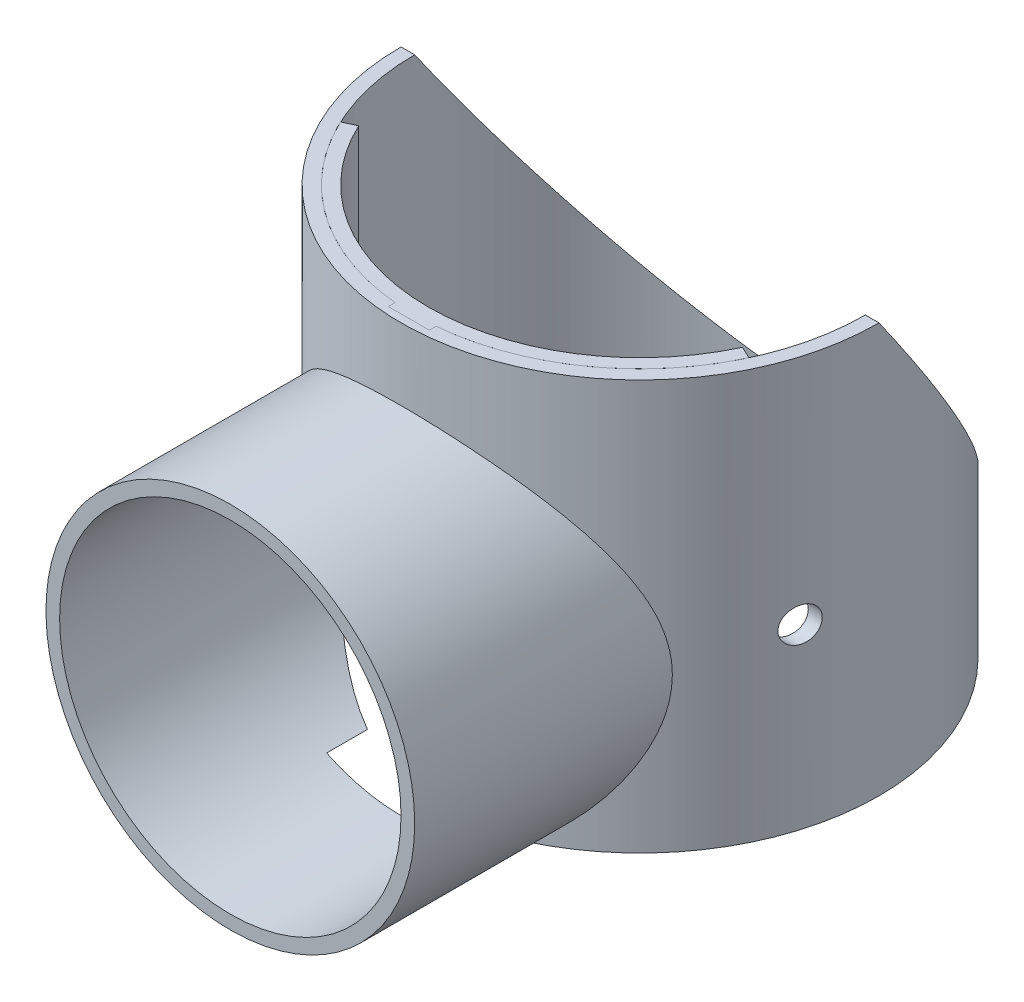
SolidWorks part; units mm, degrees
ref_plane "Спереди" through (0, 0, 0) normal (0, 0, 1) x (1, 0, 0)
ref_plane "Сверху" through (0, 0, 0) normal (0, 1, 0) x (1, 0, 0)
ref_plane "Справа" through (0, 0, 0) normal (1, 0, 0) x (0, 0, -1)
sketch "Эскиз1" plane through (0, 0, 0) normal (0, 1, 0) x (1, 0, 0)
  circle A0 centre (0, 0) radius 35
  dimension "D1" = 70
extrude "Вытянуть1" add sketch "Эскиз1" along normal blind 60
sketch "Эскиз2" plane through (0, 0, 0) normal (0, 0, 1) x (1, 0, 0)
  circle A0 centre (0, 22.5) radius 27
  dimension "D1" = 54
  dimension "D2" = 22.5
extrude "Вытянуть2" cut sketch "Эскиз2" along normal up to next
sketch "Эскиз3" plane through (0, 0, 0) normal (1, 0, 0) x (0, 0, -1)
  line L2 (35, 60) -> (-35, 60) construction
  line L7 (35, 10) -> (0, 60)
  line L8 (35, 0) -> (35, 60) construction
  line L9 (0, 60) -> (35, 60)
  line L10 (35, 60) -> (35, 10)
  dimension "D1" = 10
extrude "Вытянуть3" cut sketch "Эскиз3" against normal through all and the other way through all
sketch "Эскиз4" plane through (0, 0, 0) normal (0, 1, 0) x (1, 0, 0)
  circle A0 centre (0, 0) radius 33
  dimension "D1" = 66
extrude "Вытянуть5" cut sketch "Эскиз4" along normal through all
sketch "Эскиз5" plane through (0, 0, 0) normal (1, 0, 0) x (0, 0, -1)
  line L1 (0, 0) -> (0, 81.9672) construction
  circle A0 centre (-10, 26) radius 2.5
  dimension "D1" = 5
  dimension "D2" = 26
  dimension "D3" = 10
extrude "Вытянуть6" cut sketch "Эскиз5" against normal through all and the other way through all
sketch "Эскиз7" plane through (0, 0, 0) normal (0, 1, 0) x (1, 0, 0)
  line L0 (0, 21.1132) -> (0, -35) construction
  line L1 (-3, -32.8634) -> (-3, -33.8634)
  line L2 (-3, -33.8634) -> (3, -33.8634)
  line L3 (3, -33.8634) -> (3, -32.8634)
  arc A0 (-35, 0) -> (35, 0) centre (0, 0) ccw construction
  arc A1 (-3, -32.8634) -> (3, -32.8634) centre (0, 0) ccw
  arc A2 (-33, 0) -> (33, 0) centre (0, 0) ccw construction
  dimension "D1" = 3
  dimension "D2" = 3
  dimension "D3" = 1
extrude "Вытянуть9" cut sketch "Эскиз7" against normal blind 2 and the other way through all
sketch "Эскиз11" plane through (0, 0, 0) normal (0, 0, 1) x (1, 0, 0)
  circle A0 centre (0, 22.5) radius 27
  dimension "D1" = 54
extrude "Вытянуть11" add sketch "Эскиз11" along normal blind 60 separate body
sketch "Эскиз12" plane through (0, 0, 0) normal (0, 1, 0) x (1, 0, 0)
  circle A0 centre (0, 0) radius 31
  dimension "D1" = 62
extrude "Вытянуть12" cut sketch "Эскиз12" against normal through all and the other way through all
sketch "Эскиз8" plane through (0, 0, 0) normal (0, 1, 0) x (1, 0, 0)
  line L0 (-3, -33.8634) -> (-3, -32.8634)
  line L1 (-3, -33.8634) -> (3, -33.8634)
  line L2 (3, -33.8634) -> (3, -32.8634)
  line L3 (-28.0955, -13.1012) -> (-29.9082, -13.9464)
  line L4 (0, 0) -> (-29.9082, -13.9464) construction
  line L5 (0, 0) -> (29.9082, -13.9464) construction
  line L6 (0, 0) -> (0, -26.0941) construction
  line L7 (28.0955, -13.1012) -> (29.9082, -13.9464)
  arc A0 (-29.9082, -13.9464) -> (-3, -32.8634) centre (0, 0) ccw
  arc A1 (-33, 0) -> (-3, -32.8634) centre (0, 0) ccw construction
  arc A2 (29.9082, -13.9464) -> (3, -32.8634) centre (0, 0) cw
  arc A3 (3, -32.8634) -> (33, 0) centre (0, 0) ccw construction
  arc A4 (-28.0955, -13.1012) -> (28.0955, -13.1012) centre (0, 0) ccw
  dimension "D1" = 65
  dimension "D2" = 65
  dimension "D3" = 2
extrude "Вытянуть10" add sketch "Эскиз8" along normal blind 60
sketch "Эскиз13" plane through (0, 0, 60) normal (0, 0, 1) x (1, 0, 0)
  circle A0 centre (0, 22.5) radius 25
  dimension "D1" = 50
extrude "Вытянуть13" cut sketch "Эскиз13" against normal up to next
sketch "Эскиз14" plane through (0, 0, 0) normal (1, 0, 0) x (0, 0, -1)
  line L0 (-60, -4.5) -> (-31, -4.5) construction
  line L1 (0, 0) -> (-35, 0)
  line L2 (0, 0) -> (0, -4.5)
  line L3 (0, -4.5) -> (-35, -4.5)
  line L4 (-35, 0) -> (-35, -4.5)
extrude "Вытянуть14" cut sketch "Эскиз14" against normal through all and the other way through all
